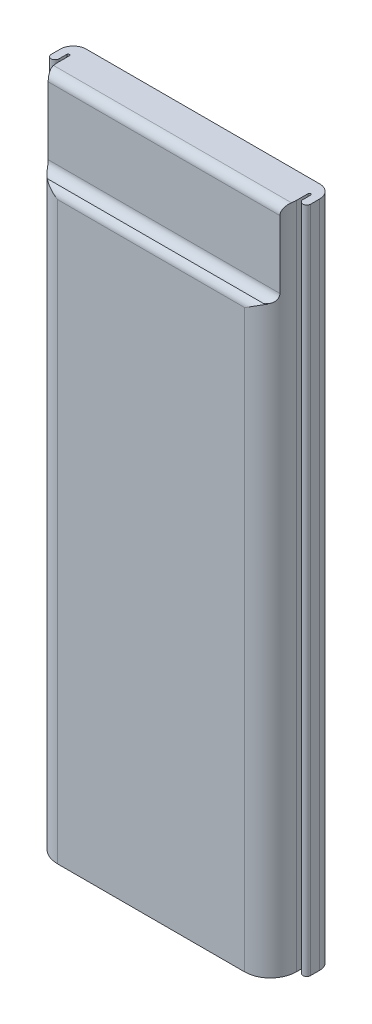
SolidWorks part; units mm, degrees
ref_plane "Front" through (0, 0, 0) normal (0, 0, 1) x (1, 0, 0)
ref_plane "Top" through (0, 0, 0) normal (0, 1, 0) x (1, 0, 0)
ref_plane "Right" through (0, 0, 0) normal (1, 0, 0) x (0, 0, -1)
sketch "Эскиз1" plane through (0, 0, 0) normal (0, 1, 0) x (1, 0, 0)
  line L0 (-9, 0) -> (9, 0)
  line L1 (-7.2, -4) -> (7.2, -4)
  line L2 (-10, -1) -> (-10, -1.7)
  line L3 (10, -1) -> (10, -1.7)
  line L4 (-9.2, -2) -> (-9.2, -1.1)
  line L5 (9.2, -1.1) -> (9.2, -2)
  line L6 (9.4, -1.7) -> (9.4, -1.1)
  line L7 (-9.4, -1.7) -> (-9.4, -1.1)
  arc A0 (-9, 0) -> (-10, -1) centre (-9, -1) ccw
  arc A1 (9, 0) -> (10, -1) centre (9, -1) cw
  arc A2 (-9.2, -2) -> (-7.2, -4) centre (-7.2, -2) ccw
  arc A3 (9.2, -2) -> (7.2, -4) centre (7.2, -2) cw
  arc A4 (10, -1.7) -> (9.4, -1.7) centre (9.7, -1.7) cw
  arc A5 (9.2, -1.1) -> (9.4, -1.1) centre (9.3, -1.1) cw
  arc A6 (-10, -1.7) -> (-9.4, -1.7) centre (-9.7, -1.7) ccw
  arc A7 (-9.2, -1.1) -> (-9.4, -1.1) centre (-9.3, -1.1) ccw
  point P20 (9.3, -1)
  point P21 (9.7, -2)
  point P27 (-9.3, -1)
  point P28 (-9.7, -2)
  dimension "D1" = 20
  dimension "D3" = 2
  dimension "D4" = 1
  dimension "D5" = 0.3
  dimension "D6" = 0.1
  dimension "D2" = 4
extrude "Бобышка-Вытянуть1" add sketch "Эскиз1" along normal mid plane 51.5
sketch "Эскиз2" plane through (0, 0, 0) normal (1, 0, 0) x (0, 0, -1)
  line L0 (-3, 25.1) -> (-3, 19.9)
  line L1 (-3.65, 19.25) -> (-3.35, 19.25)
  line L2 (-4, 25.75) -> (-4, 18.6)
  line L3 (-4, 25.75) -> (-4, -25.75) construction
  line L6 (-4, 25.75) -> (-2.35, 25.75)
  line L7 (0, 25.75) -> (-1, 25.75) construction
  arc A0 (-3, 19.9) -> (-3.65, 19.25) centre (-3.65, 19.9) cw
  arc A1 (-3.35, 19.25) -> (-4, 18.6) centre (-3.35, 18.6) ccw
  arc A2 (-2.35, 25.75) -> (-3, 25.1) centre (-2.35, 25.1) ccw
  dimension "D1" = 0.65
  dimension "D2" = 3
  dimension "D3" = 6.5
extrude "Вырез-Вытянуть1" cut sketch "Эскиз2" against normal up to next and the other way up to next
